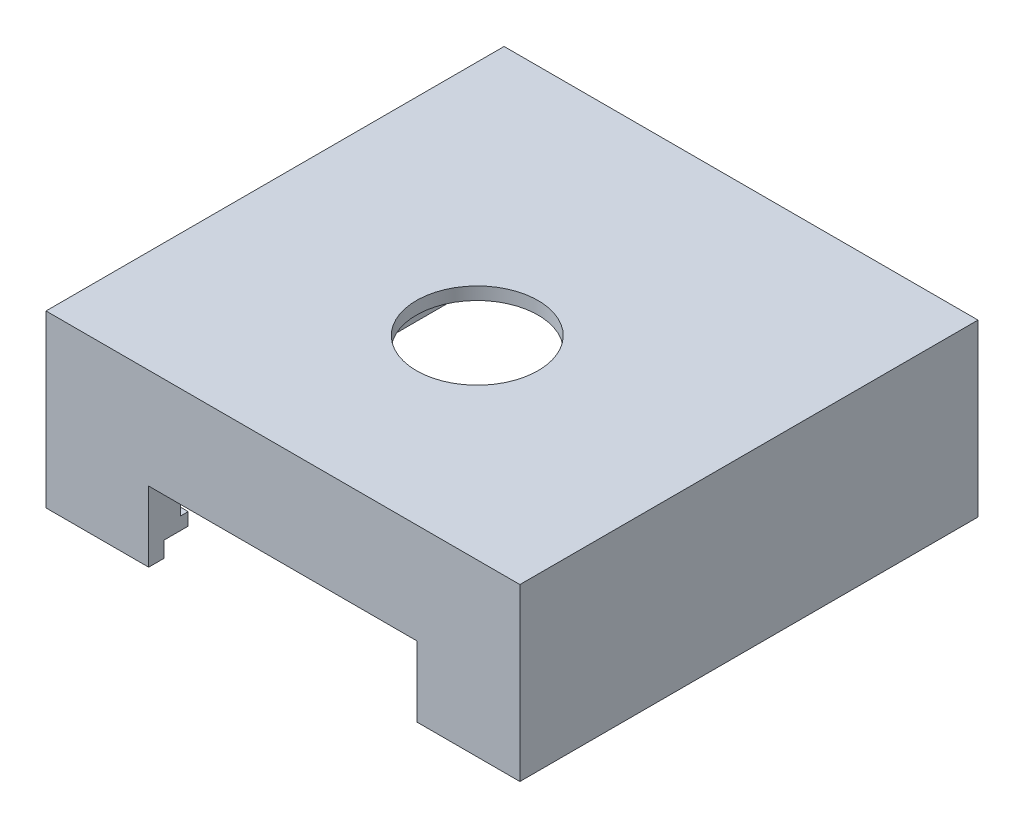
SolidWorks part; units mm, degrees
ref_plane "Front Plane" through (0, 0, 0) normal (0, 0, 1) x (1, 0, 0)
ref_plane "Top Plane" through (0, 0, 0) normal (0, 1, 0) x (1, 0, 0)
ref_plane "Right Plane" through (0, 0, 0) normal (1, 0, 0) x (0, 0, -1)
sketch "Sketch1" plane through (0, 0, 0) normal (0, 1, 0) x (1, 0, 0)
  line L0 (0, 0) -> (0, 2) construction
  line L1 (-12.5, 12) -> (12.5, 12)
  line L2 (-12.5, 12) -> (-12.5, -12)
  line L3 (-12.5, -12) -> (12.5, -12)
  line L4 (12.5, 12) -> (12.5, -12)
  line L5 (-12.5, 12) -> (12.5, -12) construction
  line L6 (-12.5, -12) -> (12.5, 12) construction
  line L7 (-4.2, 2) -> (4.2, 2)
  line L8 (-4.2, 2) -> (-4.2, -6.4)
  line L9 (-4.2, -6.4) -> (4.2, -6.4)
  line L10 (4.2, 2) -> (4.2, -6.4)
  line L11 (-4.2, -2.2) -> (4.2, -2.2) construction
  line L12 (0, 0) -> (0, -13.8286) construction
  line L13 (-8, -12) -> (8, -12)
  line L14 (-8, -12) -> (-8, -13.8286)
  line L15 (-8, -13.8286) -> (8, -13.8286)
  line L16 (8, -12) -> (8, -13.8286)
  line L17 (11.7, 10.09) -> (12.5, 10.09) construction
  line L18 (10.59, 11.2) -> (10.59, 12) construction
  line L19 (10.59, 8.98) -> (10.59, -1.2) construction
  circle A0 centre (0, -2.2) radius 3.5
  circle A1 centre (10.59, 10.09) radius 1.11
  circle A2 centre (-10.59, 10.09) radius 1.11
  circle A3 centre (10.59, -2.31) radius 1.11
  circle A4 centre (-10.59, -2.31) radius 1.11
  point P0 (0, 0)
  dimension "D5" = 7
  dimension "D7" = 2.22
  dimension "D1" = 25
  dimension "D2" = 24
  dimension "D3" = 14
  dimension "D4" = 5.6
  dimension "D6" = 16
  dimension "D8" = 0.8
  dimension "D9" = 0.8
  dimension "D10" = 10.18
sketch "Sketch2" plane through (0, 0, 0) normal (0, 1, 0) x (1, 0, 0)
  line L0 (-12.5, 12) -> (-12.5, -12) construction
  line L1 (13, -12.5) -> (-13, -12.5)
  line L2 (13, -12.5) -> (13, 12.5)
  line L3 (13, 12.5) -> (-13, 12.5)
  line L4 (-13, -12.5) -> (-13, 12.5)
  line L5 (13, -12.5) -> (-13, 12.5) construction
  line L6 (13, 12.5) -> (-13, -12.5) construction
  line L7 (12.5, 12) -> (12.5, -12) construction
  line L8 (-12.5, 12) -> (12.5, 12) construction
  line L9 (-12.5, -12) -> (12.5, -12) construction
  point P0 (0, 0)
  dimension "D1" = 0.5
  dimension "D2" = 0.5
  dimension "D3" = 0.5
  dimension "D4" = 0.5
extrude "Boss-Extrude1" add sketch "Sketch2" along normal blind 0.8
sketch "Sketch3" plane through (0, 0.8, 0) normal (0, 1, 0) x (1, 0, 0)
  circle A0 centre (0, -2.2) radius 3.85
  circle A1 centre (0, -2.2) radius 3.5 construction
  dimension "D1" = 0.35
extrude "Cut-Extrude1" cut sketch "Sketch3" against normal through all
sketch "Sketch4" plane through (0, 0, 0) normal (0, -1, 0) x (1, 0, 0)
  line L0 (-12.5, 12) -> (12.5, -12) construction
  line L1 (15, -14.5) -> (-15, -14.5)
  line L2 (15, -14.5) -> (15, 14.5)
  line L3 (15, 14.5) -> (-15, 14.5)
  line L4 (-15, -14.5) -> (-15, 14.5)
  line L5 (15, -14.5) -> (-15, 14.5) construction
  line L6 (15, 14.5) -> (-15, -14.5) construction
  line L7 (-13, -12.5) -> (-13, 12.5) construction
  line L8 (-13, 12.5) -> (13, 12.5) construction
  line L10 (13, -12.5) -> (-13, -12.5)
  line L11 (13, -12.5) -> (13, 12.5)
  line L12 (13, 12.5) -> (-13, 12.5)
  line L13 (-13, -12.5) -> (-13, 12.5)
  line L14 (13, -12.5) -> (-13, 12.5) construction
  line L15 (13, 12.5) -> (-13, -12.5) construction
  point P0 (0, 0)
  point P11 (0, 0)
  dimension "D1" = 2
  dimension "D2" = 2
extrude "Boss-Extrude2" add sketch "Sketch4" along normal blind 8.2 and the other way up to surface (0.8 mm away) other way up to face at (0, 0.8, 6.05)
sketch "Sketch5" plane through (0, -8.2, 0) normal (0, -1, 0) x (1, 0, 0)
  line L0 (-13, -12.5) -> (-13, 12.5) construction
  line L1 (12.5, -12) -> (-12.5, -12)
  line L2 (12.5, -12) -> (12.5, 12)
  line L3 (12.5, 12) -> (-12.5, 12)
  line L4 (-12.5, -12) -> (-12.5, 12)
  line L5 (12.5, -12) -> (-12.5, 12) construction
  line L6 (12.5, 12) -> (-12.5, -12) construction
  line L7 (13, 12.5) -> (-13, 12.5) construction
  line L8 (15, -14.5) -> (15, 14.5) construction
  line L9 (-15, -14.5) -> (15, -14.5) construction
  line L10 (-15, 14.5) -> (-15, -14.5) construction
  line L11 (15, 14.5) -> (-15, 14.5) construction
  line L12 (15, -14.5) -> (15, 14.5)
  line L13 (-15, -14.5) -> (15, -14.5)
  line L14 (-15, 14.5) -> (-15, -14.5)
  line L15 (15, 14.5) -> (-15, 14.5)
  point P0 (0, 0)
  dimension "D1" = 0.5
  dimension "D2" = 0.5
extrude "Boss-Extrude3" add sketch "Sketch5" along normal blind 0.8
sketch "Sketch6" plane through (0, -9, 0) normal (0, -1, 0) x (1, 0, 0)
  line L1 (15, -14.5) -> (-15, -14.5)
  line L2 (15, -14.5) -> (15, 14.5)
  line L3 (15, 14.5) -> (-15, 14.5)
  line L4 (-15, -14.5) -> (-15, 14.5)
  line L5 (15, -14.5) -> (-15, 14.5) construction
  line L6 (15, 14.5) -> (-15, -14.5) construction
  line L7 (14, -13.5333) -> (-14, -13.5333)
  line L8 (14, -13.5333) -> (14, 13.5333)
  line L9 (14, 13.5333) -> (-14, 13.5333)
  line L10 (-14, -13.5333) -> (-14, 13.5333)
  line L11 (14, -13.5333) -> (-14, 13.5333) construction
  line L12 (14, 13.5333) -> (-14, -13.5333) construction
  point P0 (0, 0)
  point P7 (0, 0)
  dimension "D1" = 1
extrude "Boss-Extrude4" add sketch "Sketch6" along normal blind 1
sketch "Sketch7" plane through (0, 0, 0) normal (0, -1, 0) x (1, 0, 0)
  line L0 (0, 0) -> (0, 13.8286) construction
  line L1 (-10.3968, 11.3299) -> (10.3968, 11.3299)
  line L2 (-10.3968, 11.3299) -> (-10.3968, 7.8262)
  line L3 (-6.36, 7.8262) -> (6.36, 7.8262)
  line L4 (10.3968, 11.3299) -> (10.3968, 7.8262)
  line L5 (-10.3968, 11.3299) -> (10.3968, 7.8262) construction
  line L6 (-10.3968, 7.8262) -> (10.3968, 11.3299) construction
  line L7 (-10.3968, 7.8262) -> (-10.3968, -10.6444)
  line L8 (-10.3968, -10.6444) -> (-6.36, -10.6444)
  line L9 (-6.36, -10.6444) -> (-6.36, 7.8262)
  line L10 (0, 4.8176) -> (0, -7.0645) construction
  line L11 (10.3968, -10.6444) -> (6.36, -10.6444)
  line L12 (10.3968, 7.8262) -> (10.3968, -10.6444)
  line L13 (6.36, -10.6444) -> (6.36, 7.8262)
  point P0 (0, 9.578)
extrude "Boss-Extrude5" add sketch "Sketch7" along normal blind 4.55
sketch "Sketch8" plane through (0, -10, 0) normal (0, -1, 0) x (1, 0, 0)
  line L0 (15, 14.5) -> (-15, 14.5) construction
  line L1 (-8.5, 14.5) -> (8.5, 14.5)
  line L2 (-8.5, 14.5) -> (-8.5, 10.5715)
  line L3 (-8.5, 10.5715) -> (8.5, 10.5715)
  line L4 (8.5, 14.5) -> (8.5, 10.5715)
  line L5 (0, 0) -> (0, 14.5) construction
  line L6 (-12.5, -12) -> (12.5, 12) construction
  line L7 (8, 12) -> (8, 13.8286) construction
  dimension "D1" = 0.5
extrude "Cut-Extrude2" cut sketch "Sketch8" against normal offset from surface (4.45 mm away) 1 up to face at (0, -4.55, -0.5332)
sketch "Sketch9" plane through (0, -4.55, 0) normal (0, -1, 0) x (1, 0, 0)
  line L0 (-10.3968, 11.3299) -> (-10.3968, -10.6444) construction
  line L1 (-10.3968, 5.7316) -> (-6.36, 5.7316)
  line L2 (-10.3968, 5.7316) -> (-10.3968, -6.5314)
  line L3 (-10.3968, -6.5314) -> (-6.36, -6.5314)
  line L4 (-6.36, 5.7316) -> (-6.36, -6.5314)
  line L5 (-6.36, -10.6444) -> (-6.36, 7.8262) construction
  line L6 (0, 6.9122) -> (0, -4.551) construction
  line L7 (10.3968, -6.5314) -> (6.36, -6.5314)
  line L8 (6.36, 5.7316) -> (6.36, -6.5314)
  line L9 (10.3968, 5.7316) -> (6.36, 5.7316)
  line L10 (10.3968, 5.7316) -> (10.3968, -6.5314)
extrude "Cut-Extrude3" cut sketch "Sketch9" against normal up to surface (4.55 mm away) up to face at (0, 0, 0)
